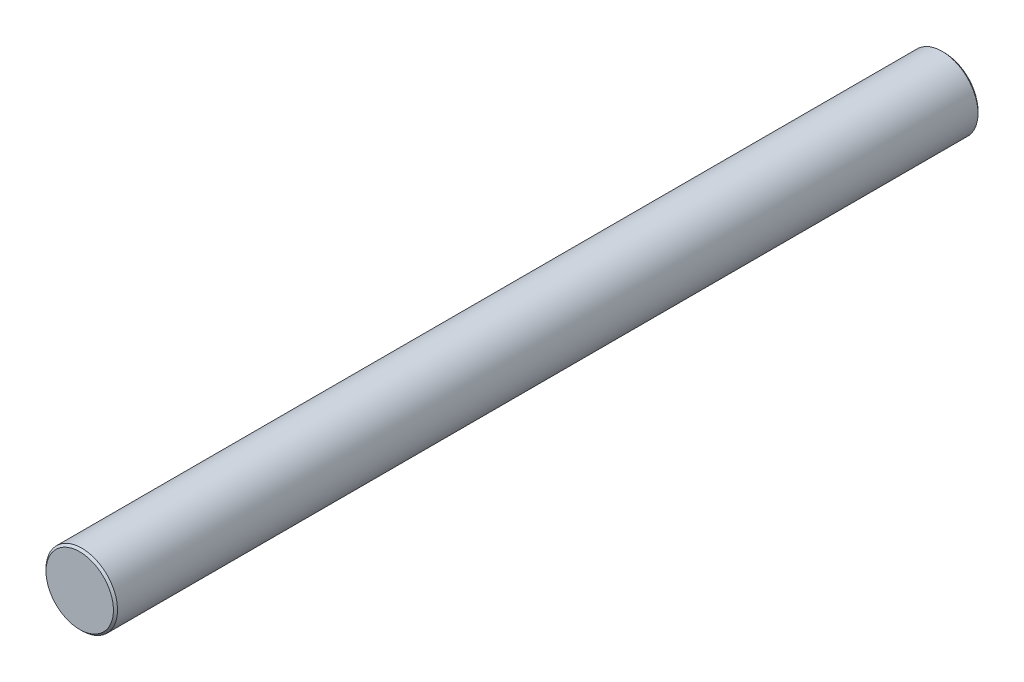
SolidWorks part; units mm, degrees
ref_plane "Front Plane" through (0, 0, 0) normal (0, 0, 1) x (1, 0, 0)
ref_plane "Top Plane" through (0, 0, 0) normal (0, 1, 0) x (1, 0, 0)
ref_plane "Right Plane" through (0, 0, 0) normal (1, 0, 0) x (0, 0, -1)
sketch "Sketch1" plane through (0, 0, 0) normal (0, 0, 1) x (1, 0, 0)
  circle A0 centre (0, 0) radius 3.475
  dimension "D1" = 6.95
extrude "Boss-Extrude1" add sketch "Sketch1" along normal mid plane 84
chamfer "Chamfer1" distance 0.2 angle 45 2 edges at (3.475, 0, 42) (3.475, 0, -42)
